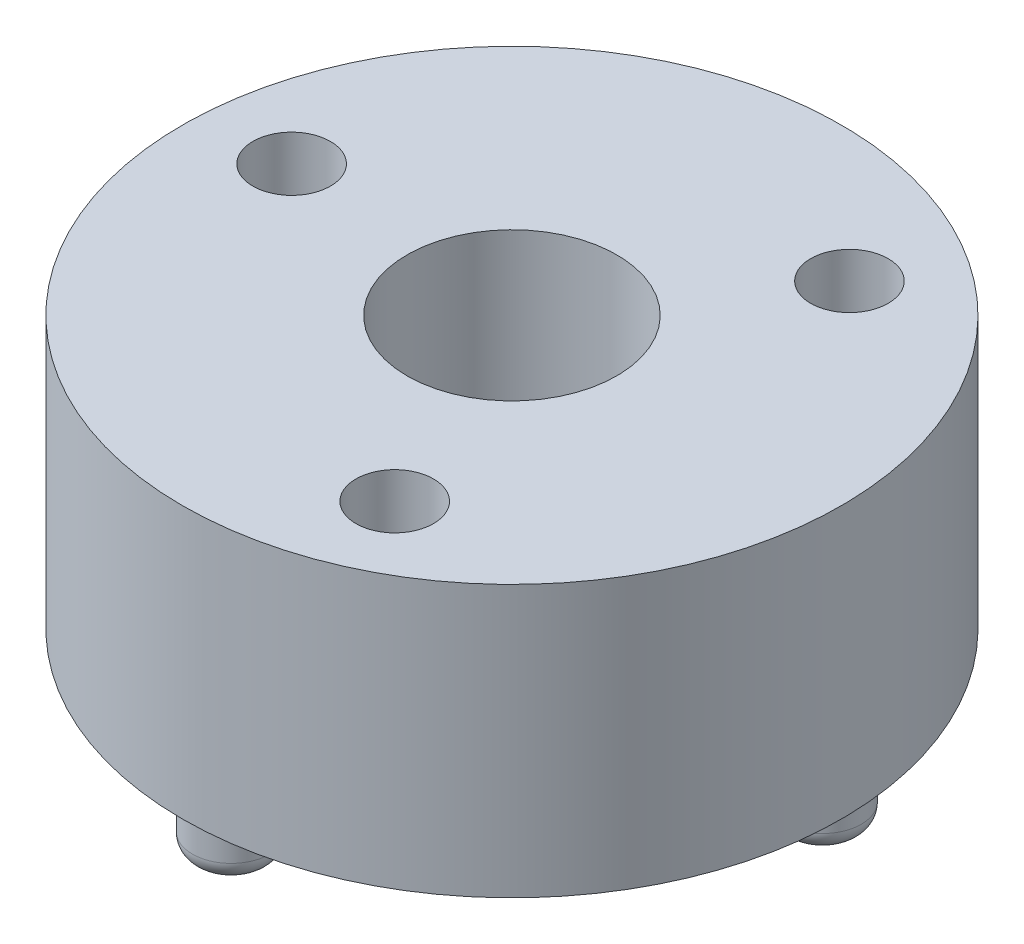
SolidWorks part; units mm, degrees
ref_plane "Front Plane" through (0, 0, 0) normal (0, 0, 1) x (1, 0, 0)
ref_plane "Top Plane" through (0, 0, 0) normal (0, 1, 0) x (1, 0, 0)
ref_plane "Right Plane" through (0, 0, 0) normal (1, 0, 0) x (0, 0, -1)
sketch "Sketch1" plane through (0, 0, 0) normal (0, 1, 0) x (1, 0, 0)
  circle A0 centre (0, 0) radius 8.5
extrude "Cylinder" add sketch "Sketch1" along normal blind 7
sketch "Sketch2" plane through (0, 7, 0) normal (0, 1, 0) x (1, 0, 0)
  circle A0 centre (0, 0) radius 2.705
extrude "Luer Hole" cut sketch "Sketch2" against normal blind 5
sketch "Sketch3" plane through (0, 0, 0) normal (0, -1, 0) x (1, 0, 0)
  line L0 (0, 0) -> (0, 6.25) construction
  circle A0 centre (0, 0) radius 6.25 construction
  circle A1 centre (-1.0853, 6.155) radius 1
  circle A2 centre (5.8731, -2.1376) radius 1
  circle A4 centre (-4.7878, -4.0174) radius 1 [skipped]
  point P11 (0, 0)
  dimension "D1" = 3
extrude "Dowel Pins" add sketch "Sketch3" along normal blind 2.5
sketch "Sketch4" plane through (0, 0, 0) normal (0, -1, 0) x (1, 0, 0)
  line L0 (0, 0) -> (0, -6.25) construction
  line L1 (-6.2262, -0.5447) -> (0, 0) construction
  line L2 (0, 0) -> (0, -2.9098) construction
  line L3 (0, 0) -> (-6.25, 0) construction
  circle A0 centre (0, 0) radius 6.25 construction
  circle A1 centre (-6.2262, -0.5447) radius 1
  circle A2 centre (2.6414, 5.6644) radius 1
  circle A3 centre (3.5849, -5.1197) radius 1
  point P11 (0, 0)
  dimension "D1" = 3
extrude "Screw Holes" cut sketch "Sketch4" against normal through all
fillet "Fillet Dowel Pins" radius 0.5 2 edges at (-1.0853, -2.5, 5.155) (5.8731, -2.5, -3.1376)
